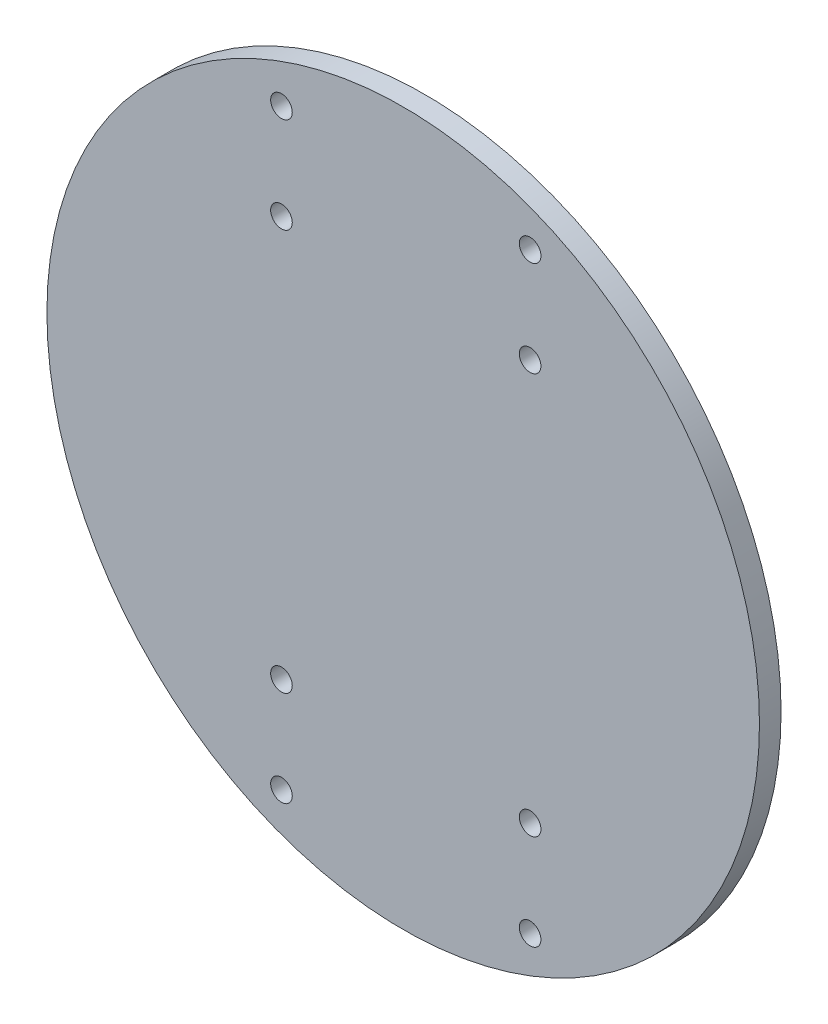
SolidWorks part; units mm, degrees
ref_plane "Alzado" through (0, 0, 0) normal (0, 0, 1) x (1, 0, 0)
ref_plane "Planta" through (0, 0, 0) normal (0, 1, 0) x (1, 0, 0)
ref_plane "Vista lateral" through (0, 0, 0) normal (1, 0, 0) x (0, 0, -1)
sketch "Croquis1" plane through (0, 0, 0) normal (0, 0, 1) x (1, 0, 0)
  circle A0 centre (0, 0) radius 82.42
  dimension "D1" = 164.84
extrude "Saliente-Extruir1" add sketch "Croquis1" along normal blind 5
sketch "Croquis3" plane through (0, 0, 5) normal (0, 0, 1) x (1, 0, 0)
  line L0 (-32.76, 72.96) -> (32.76, 72.96) construction
  line L1 (-32.76, 72.96) -> (32.76, 72.96) construction
  line L2 (32.76, 72.96) -> (32.76, -72.96)
  line L3 (-32.76, 72.96) -> (32.76, 72.96)
  line L4 (-32.76, 72.96) -> (-32.76, -72.96)
  line L5 (-32.76, -72.96) -> (32.76, -72.96)
  line L7 (-32.76, -72.96) -> (-32.76, -68.49) construction
  line L8 (-32.76, -72.96) -> (-28.16, -72.96) construction
  line L9 (-32.76, -68.49) -> (-28.16, -68.49) construction
  line L10 (-28.16, -68.49) -> (-28.16, -72.96) construction
  line L11 (-28.16, -68.49) -> (-28.16, -46.39) construction
  line L12 (-28.16, -46.39) -> (29.36, -46.39) construction
  line L13 (29.36, -46.39) -> (29.36, -68.49) construction
  line L14 (-28.16, -68.49) -> (29.36, -68.49) construction
  line L15 (0, -72.96) -> (0, 72.96) construction
  line L16 (-32.76, 0) -> (32.76, 0) construction
  line L17 (-28.16, 68.49) -> (-32.76, 68.49) construction
  line L18 (-28.16, 68.49) -> (-28.16, 72.96) construction
  circle A0 centre (-28.16, -68.49) radius 2.5
  circle A1 centre (-28.16, -46.39) radius 2.5
  circle A2 centre (0, 0) radius 79.9774
  circle A3 centre (29.36, -46.39) radius 2.5
  circle A4 centre (29.36, -68.49) radius 2.5
  circle A5 centre (29.36, 68.49) radius 2.5
  circle A6 centre (-28.16, 68.49) radius 2.5
  circle A7 centre (29.36, 46.39) radius 2.5
  circle A8 centre (-28.16, 46.39) radius 2.5
  dimension "D5" = 5
  dimension "D7" = 5
  dimension "D9" = 5
  dimension "D11" = 5
  dimension "D1" = 145.92
  dimension "D2" = 65.52
  dimension "D3" = 4.47
  dimension "D4" = 4.6
  dimension "D6" = 22.1
  dimension "D8" = 57.52
  dimension "D10" = 22.1
extrude "Cortar-Extruir1" cut sketch "Croquis3" along normal mid plane 10 contours A7 | A6 | A3 | A1 | A4 | A5 | A8 | A0
